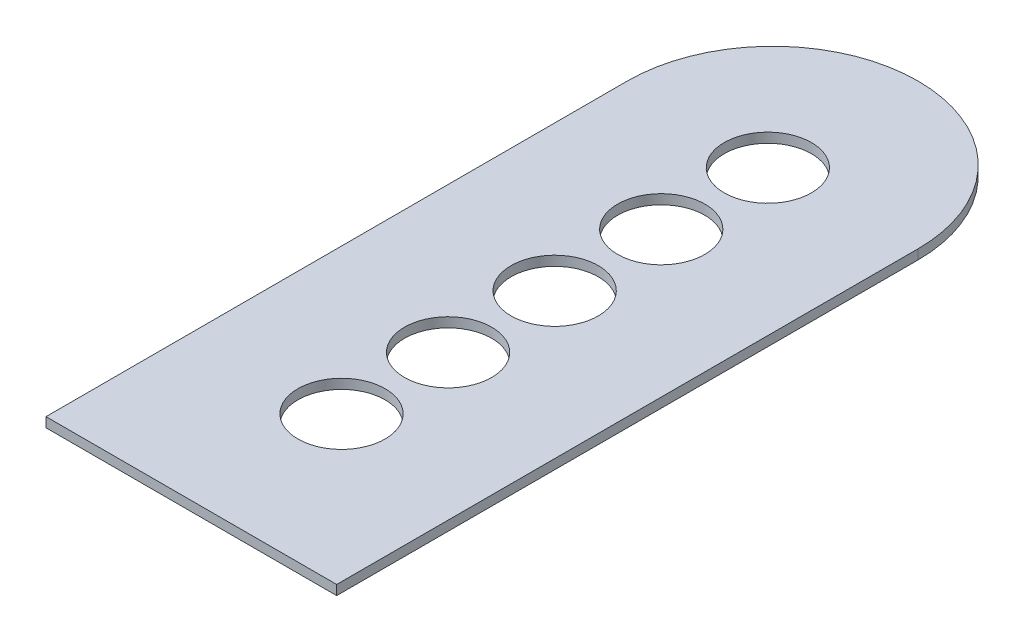
SolidWorks part; units mm, degrees
ref_plane "Plan de face" through (0, 0, 0) normal (0, 0, 1) x (1, 0, 0)
ref_plane "Plan de dessus" through (0, 0, 0) normal (0, 1, 0) x (1, 0, 0)
ref_plane "Plan de droite" through (0, 0, 0) normal (1, 0, 0) x (0, 0, -1)
sketch "Esquisse1" plane through (0, 0, 0) normal (0, 1, 0) x (1, 0, 0)
  line L0 (0, 0) -> (0, 600)
  line L1 (0, 0) -> (300, 0)
  line L2 (150, 0) -> (150, 750) construction
  line L3 (300, 0) -> (300, 600)
  line L4 (0, 600) -> (0, 750) construction
  arc A0 (300, 600) -> (0, 600) centre (150, 600) ccw
  circle A1 centre (150, 155) radius 45
  circle A2 centre (150, 265) radius 45
  circle A3 centre (150, 375) radius 45
  circle A4 centre (150, 485) radius 45
  circle A5 centre (150, 595) radius 45
  arc A7 (0, 150) -> (150, 0) centre (150, 150) ccw construction
  arc A8 (150, 0) -> (300, 150) centre (150, 150) ccw construction
  point P6 (150, 155)
  point P8 (150, 265)
  point P10 (150, 485)
  point P11 (150, 595)
  dimension "D10" = 90
  dimension "D11" = 90
  dimension "D12" = 90
  dimension "D13" = 90
  dimension "D14" = 90
  dimension "D1" = 750
  dimension "D2" = 150
  dimension "D3" = 150
  dimension "D4" = 150
  dimension "D5" = 155
  dimension "D6" = 110
  dimension "D7" = 110
  dimension "D8" = 110
  dimension "D9" = 155
extrude "Boss.-Extru.1" add sketch "Esquisse1" along normal blind 10
